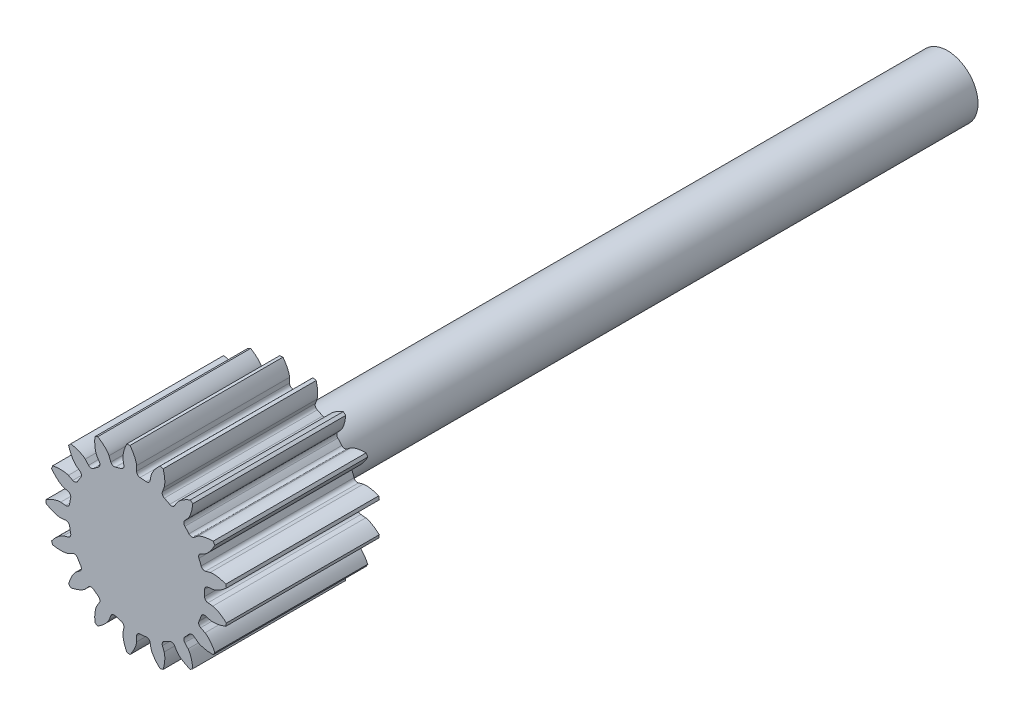
SolidWorks part; units mm, degrees
ref_plane "Front Plane" through (0, 0, 0) normal (0, 0, 1) x (1, 0, 0)
ref_plane "Top Plane" through (0, 0, 0) normal (0, 1, 0) x (1, 0, 0)
ref_plane "Right Plane" through (0, 0, 0) normal (1, 0, 0) x (0, 0, -1)
ref_axis "Gear Axis" through (0, 0, -0.2501) along (0, 0, 1)
sketch "Blank Sketch" plane through (0, 0, 0) normal (0, 0, 1) x (1, 0, 0)
  circle A0 centre (0, 0) radius 11.875
  dimension "OD" = 23.75
extrude "Blank" add sketch "Blank Sketch" along normal blind 20
sketch "Tooth Space Sketch" plane through (0, 0, 0) normal (0, 0, 1) x (1, 0, 0)
  line L0 (9.9391, 0.9485) -> (9.2957, 0.8871)
  line L1 (9.9391, -0.9485) -> (9.2957, -0.8871)
  line L2 (12.7424, 3.1457) -> (12.7424, -3.1457)
  arc A0 (9.2957, 0.8871) -> (8.8663, 0.3932) centre (9.3408, 0.4142) ccw
  arc A1 (8.8663, -0.3932) -> (9.2957, -0.8871) centre (9.3408, -0.4142) ccw
  arc A2 (8.8663, -0.3932) -> (8.8663, 0.3932) centre (0, 0) ccw
  spline S0 degree 4 poles (9.9391, 0.9485) (9.9444, 0.9491) (9.9594, 0.9511) (9.9875, 0.9561) (10.033, 0.9658) (10.0906, 0.9807) (10.1644, 1.0027) (10.2505, 1.0321) (10.344, 1.0681) (10.4445, 1.1112) (10.5435, 1.1577) (10.6412, 1.2072) (10.7373, 1.2593) (10.8523, 1.3258) (10.9883, 1.4101) (11.1441, 1.5151) (11.3169, 1.6419) (11.4885, 1.7791) (11.6537, 1.9206) (11.816, 2.0708) (11.9698, 2.2212) (12.1246, 2.3846) (12.2649, 2.5391) (12.4162, 2.7198) (12.5367, 2.8679) (12.6891, 3.071) (12.7772, 3.1933) (12.878, 3.3391) (12.9216, 3.4052) (12.9484, 3.4459) knots 0 0 0 0 0 0.005377 0.015084 0.028532 0.04661 0.064855 0.092111 0.119476 0.146842 0.174209 0.201575 0.228941 0.256307 0.307035 0.361767 0.4165 0.471232 0.525964 0.580697 0.635429 0.690161 0.744894 0.799626 0.854358 0.909091 0.954545 1 1 1 1 1 construction
  spline S1 degree 4 poles (9.9391, 0.9485) (9.9444, 0.9491) (9.9594, 0.9511) (9.9875, 0.9561) (10.033, 0.9658) (10.0906, 0.9807) (10.1644, 1.0027) (10.2505, 1.0321) (10.344, 1.0681) (10.4445, 1.1112) (10.5435, 1.1577) (10.6412, 1.2072) (10.7373, 1.2593) (10.8523, 1.3258) (10.9883, 1.4101) (11.1441, 1.5151) (11.3169, 1.6419) (11.4885, 1.7791) (11.6537, 1.9206) (11.816, 2.0708) (11.9698, 2.2212) (12.1246, 2.3846) (12.2649, 2.5391) (12.4162, 2.7198) (12.5367, 2.8679) (12.6561, 3.027) (12.7135, 3.1053) (12.7424, 3.1457) knots 0 0 0 0 0 0.005377 0.015084 0.028532 0.04661 0.064855 0.092111 0.119476 0.146842 0.174209 0.201575 0.228941 0.256307 0.307035 0.361767 0.4165 0.471232 0.525964 0.580697 0.635429 0.690161 0.744894 0.799626 0.854358 0.909091 0.909091 0.909091 0.909091 0.909091
  spline S2 degree 4 poles (9.9391, -0.9485) (9.9444, -0.9491) (9.9594, -0.9511) (9.9875, -0.9561) (10.033, -0.9658) (10.0906, -0.9807) (10.1644, -1.0027) (10.2505, -1.0321) (10.344, -1.0681) (10.4445, -1.1112) (10.5435, -1.1577) (10.6412, -1.2072) (10.7373, -1.2593) (10.8523, -1.3258) (10.9883, -1.4101) (11.1441, -1.5151) (11.3169, -1.6419) (11.4885, -1.7791) (11.6537, -1.9206) (11.816, -2.0708) (11.9698, -2.2212) (12.1246, -2.3846) (12.2649, -2.5391) (12.4162, -2.7198) (12.5367, -2.8679) (12.6891, -3.071) (12.7772, -3.1933) (12.878, -3.3391) (12.9216, -3.4052) (12.9484, -3.4459) knots 0 0 0 0 0 0.005377 0.015084 0.028532 0.04661 0.064855 0.092111 0.119476 0.146842 0.174209 0.201575 0.228941 0.256307 0.307035 0.361767 0.4165 0.471232 0.525964 0.580697 0.635429 0.690161 0.744894 0.799626 0.854358 0.909091 0.954545 1 1 1 1 1 construction
  spline S3 degree 4 poles (9.9391, -0.9485) (9.9444, -0.9491) (9.9594, -0.9511) (9.9875, -0.9561) (10.033, -0.9658) (10.0906, -0.9807) (10.1644, -1.0027) (10.2505, -1.0321) (10.344, -1.0681) (10.4445, -1.1112) (10.5435, -1.1577) (10.6412, -1.2072) (10.7373, -1.2593) (10.8523, -1.3258) (10.9883, -1.4101) (11.1441, -1.5151) (11.3169, -1.6419) (11.4885, -1.7791) (11.6537, -1.9206) (11.816, -2.0708) (11.9698, -2.2212) (12.1246, -2.3846) (12.2649, -2.5391) (12.4162, -2.7198) (12.5367, -2.8679) (12.6561, -3.027) (12.7135, -3.1053) (12.7424, -3.1457) knots 0 0 0 0 0 0.005377 0.015084 0.028532 0.04661 0.064855 0.092111 0.119476 0.146842 0.174209 0.201575 0.228941 0.256307 0.307035 0.361767 0.4165 0.471232 0.525964 0.580697 0.635429 0.690161 0.744894 0.799626 0.854358 0.909091 0.909091 0.909091 0.909091 0.909091
  dimension "Root" = 8.875
  dimension "Fillet" = 0.475
extrude "Tooth Space" cut sketch "Tooth Space Sketch" against normal through all both and the other way through all both
pattern_circular "Teeth" count 17 over 360 about axis through (0, 0, -0.2501) along (0, 0, 1) of "Tooth Space"
sketch "Bore Sketch" plane through (0, 0, 0) normal (0, 0, 1) x (1, 0, 0)
  circle A0 centre (0, 0) radius 4
  dimension "Bore" = 8
extrude "Bore" cut sketch "Bore Sketch" against normal through all both and the other way through all both
sketch "Sketch1" plane through (0, 0, 20) normal (0, 0, 1) x (1, 0, 0)
  circle A0 centre (0, 0) radius 4 construction
  circle A1 centre (0, 0) radius 4
extrude "Boss-Extrude1" add sketch "Sketch1" against normal blind 106
equation "\"No. of Teeth\"= 17"
equation "\"Module\"= 1.25"
equation "\"Bore Diameter\"= 8"
equation "\"Pressure Angle\"= 20"
equation "\"Outer Diameter\"= ( \"No. of Teeth\" + 2 ) * \"Module\""
equation "\"Pitch Diameter\"= \"No. of Teeth\" * \"Module\""
equation "\"Backlash\"= 0.3 * \"Module\""
equation "\"Arc Length\"= ( ( \"Module\" * pi ) / 2 + \"Backlash\" )"
equation "\"Fillet Radius\"= 0.38 * \"Module\""
equation "\"Tooth Depth\"= IIF ( \"Module\" <= 1.25 , \"Module\" * 2.4 , \"Module\" * 2.25 )"
equation "\"Face Width\"= 20"
equation "\"Root Diameter\"= \"Outer Diameter\" - 2 * \"Tooth Depth\""
equation "\"Base Diameter\"= \"Pitch Diameter\" * cos ( \"Pressure Angle\" )"
equation "\"Base Radius\"= \"Base Diameter\" / 2"
equation "\"Tooth Thickness\"= \"Module\" * pi - \"Arc Length\""
equation "\"Half Space Angle\"= ( \"Arc Length\" / \"Pitch Diameter\" ) * 180 / pi"
equation "\"Involute Fn\"= tan ( \"Pressure Angle\" ) - \"Pressure Angle\" * pi / 180"
equation "\"Flank Offset\"= \"Arc Length\" / \"Pitch Diameter\" - \"Involute Fn\""
equation "\"Tip Cap Diameter\"= \"Outer Diameter\" + 2 * \"Module\""
equation "\"Flank Start Diameter\"= IIF ( \"Base Diameter\" >= ( \"Root Diameter\" + 3 * \"Fillet Radius\" ) , \"Base Diameter\" , \"Root Diameter\" + 3 * \"Fillet Radius\" )"
equation "\"Involute t1\"= ( abs ( ( \"Flank Start Diameter\" / \"Base Diameter\" ) ^ 2 - 1 ) ) ^ 0.5"
equation "\"Involute t2\"= ( abs ( ( \"Tip Cap Diameter\" / \"Base Diameter\" ) ^ 2 - 1 ) ) ^ 0.5"
equation "\"Flank Arc Radius\"= ( \"Pitch Diameter\" / 2 ) * sin ( \"Pressure Angle\" )"
equation "\"Flank Centre Angle\"= \"Half Space Angle\" + \"Pressure Angle\""
equation "\"OD@Blank Sketch\"= \"Outer Diameter\""
equation "\"Width@Blank\"= \"Face Width\""
equation "\"Root@Tooth Space Sketch\"= \"Root Diameter\" / 2"
equation "\"Fillet@Tooth Space Sketch\"= \"Fillet Radius\""
equation "\"Count@Teeth\"= \"No. of Teeth\""
equation "\"Bore@Bore Sketch\"= \"Bore Diameter\""
